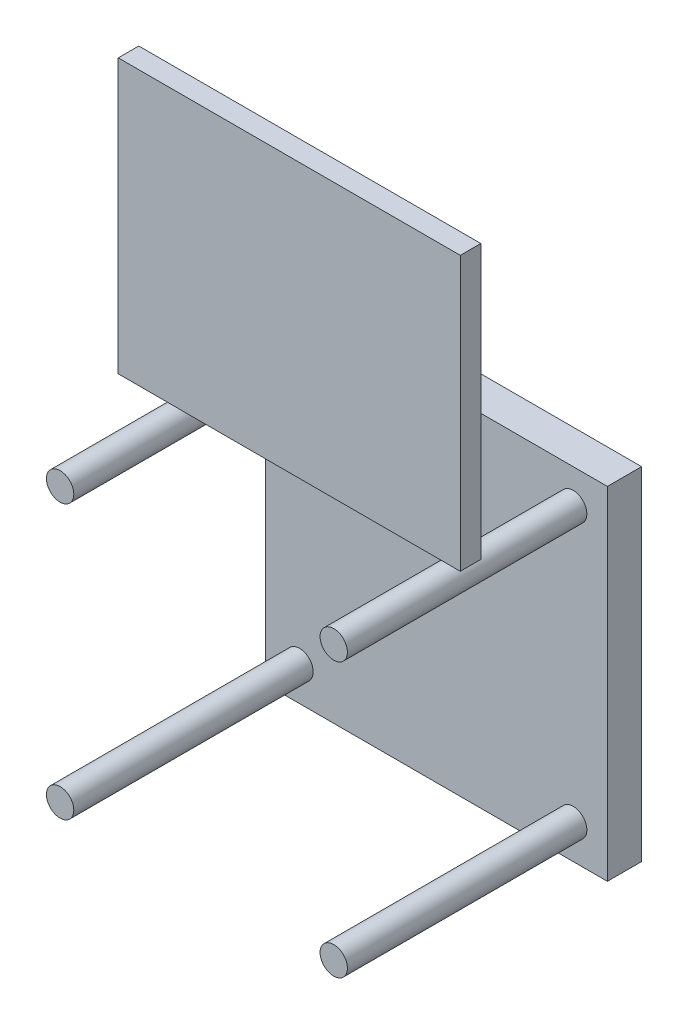
SolidWorks part; units mm, degrees
ref_plane "前视基准面" through (0, 0, 0) normal (0, 0, 1) x (1, 0, 0)
ref_plane "上视基准面" through (0, 0, 0) normal (0, 1, 0) x (1, 0, 0)
ref_plane "右视基准面" through (0, 0, 0) normal (1, 0, 0) x (0, 0, -1)
other "Configuration Table"
sketch "草图1" plane through (0, 0, 0) normal (0, 0, 1) x (1, 0, 0)
  line L1 (-250, -250) -> (250, -250)
  line L2 (-250, -250) -> (-250, 250)
  line L3 (-250, 250) -> (250, 250)
  line L4 (250, -250) -> (250, 250)
  line L5 (-250, -250) -> (250, 250) construction
  line L6 (-250, 250) -> (250, -250) construction
  point P0 (0, 0)
extrude "凸台-拉伸1" add sketch "草图1" along normal blind 50
sketch "草图2" plane through (0, 0, 0) normal (0, 0, 1) x (1, 0, 0)
  circle A0 centre (-200, -200) radius 20
extrude "凸台-拉伸2" add sketch "草图2" along normal blind 400
sketch "草图3" plane through (0, 0, 0) normal (0, 0, 1) x (1, 0, 0)
  circle A0 centre (200, -200) radius 20
extrude "凸台-拉伸3" add sketch "草图3" along normal blind 400
sketch "草图4" plane through (0, 0, 0) normal (0, 0, 1) x (1, 0, 0)
  circle A0 centre (-200, 200) radius 20
extrude "凸台-拉伸4" add sketch "草图4" along normal blind 400
sketch "草图5" plane through (0, 0, 0) normal (0, 0, 1) x (1, 0, 0)
  circle A0 centre (200, 200) radius 20
extrude "凸台-拉伸5" add sketch "草图5" along normal blind 400
sketch "草图6" plane through (0, 250, 0) normal (0, 1, 0) x (1, 0, 0)
  line L1 (-250, -265) -> (250, -265)
  line L2 (-250, -265) -> (-250, -235)
  line L3 (-250, -235) -> (250, -235)
  line L4 (250, -265) -> (250, -235)
  line L5 (-250, -265) -> (250, -235) construction
  line L6 (-250, -235) -> (250, -265) construction
  point P0 (0, -250)
extrude "凸台-拉伸6" add sketch "草图6" along normal blind 400
